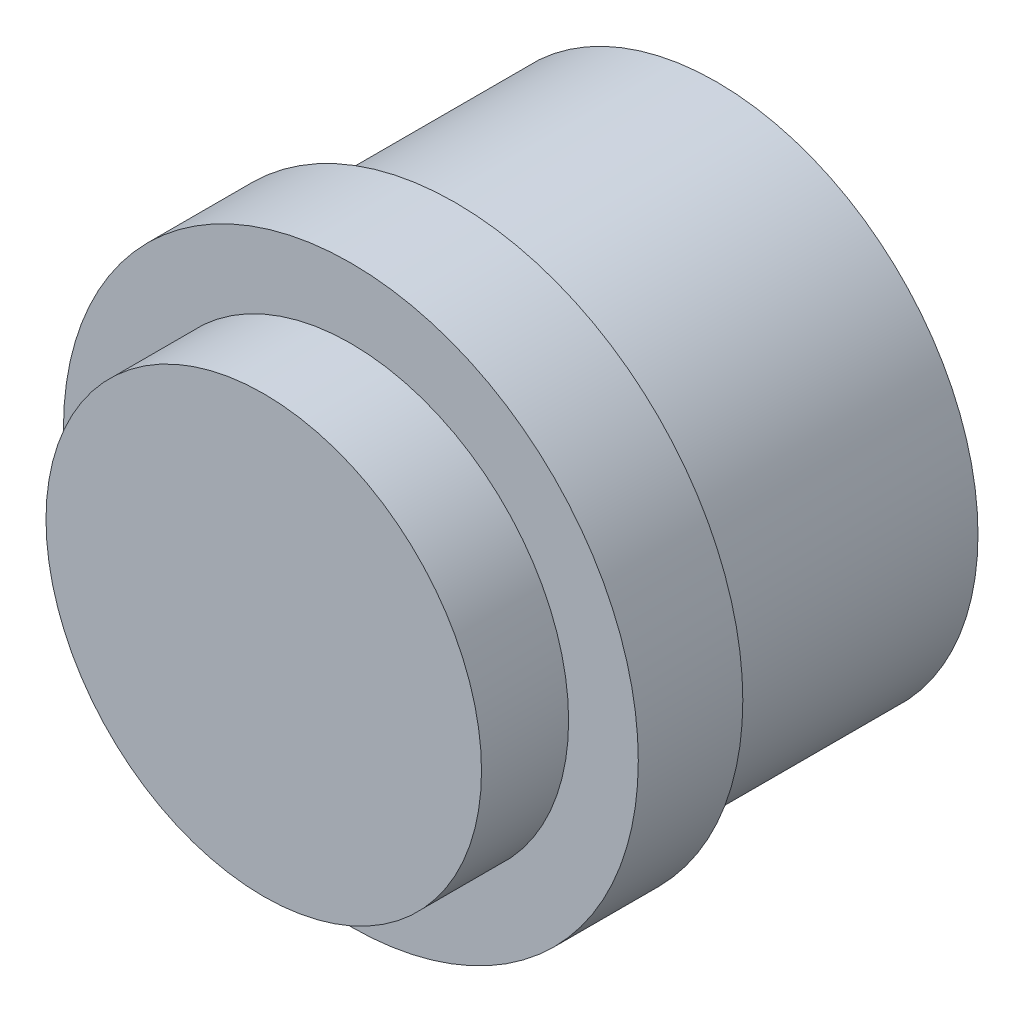
SolidWorks part; units mm, degrees
ref_plane "Front Plane" through (0, 0, 0) normal (1, 0, 0) x (0, 1, 0)
ref_plane "Top Plane" through (0, 0, 0) normal (0, 0, 1) x (0, 1, 0)
ref_plane "Right Plane" through (0, 0, 0) normal (0, 1, 0) x (-1, 0, 0)
sketch "Sketch1" plane through (0, 0, 0) normal (0, 0, 1) x (0, 1, 0)
  circle A0 centre (0, 0) radius 16.5
  dimension "D1" = 33
extrude "Boss-Extrude1" add sketch "Sketch1" along normal blind 26
sketch "Sketch2" plane through (0, 0, 26) normal (0, 0, 1) x (1, 0, 0)
  circle A0 centre (0, 0) radius 16.5
  circle A1 centre (0, 0) radius 12.5
  dimension "D1" = 25
extrude "Cut-Extrude1" cut sketch "Sketch2" against normal blind 5
sketch "Sketch3" plane through (0, 0, 0) normal (0, 0, -1) x (1, 0, 0)
  circle A0 centre (0, 0) radius 15
  circle A1 centre (0, 0) radius 16.5
  dimension "D1" = 30
extrude "Cut-Extrude2" cut sketch "Sketch3" against normal blind 15
sketch "Sketch4" plane through (0, 0, 0) normal (0, 0, -1) x (1, 0, 0)
  circle A1 centre (0, 0) radius 12.5
  dimension "D1" = 25
extrude "Cut-Extrude3" cut sketch "Sketch4" against normal blind 15
